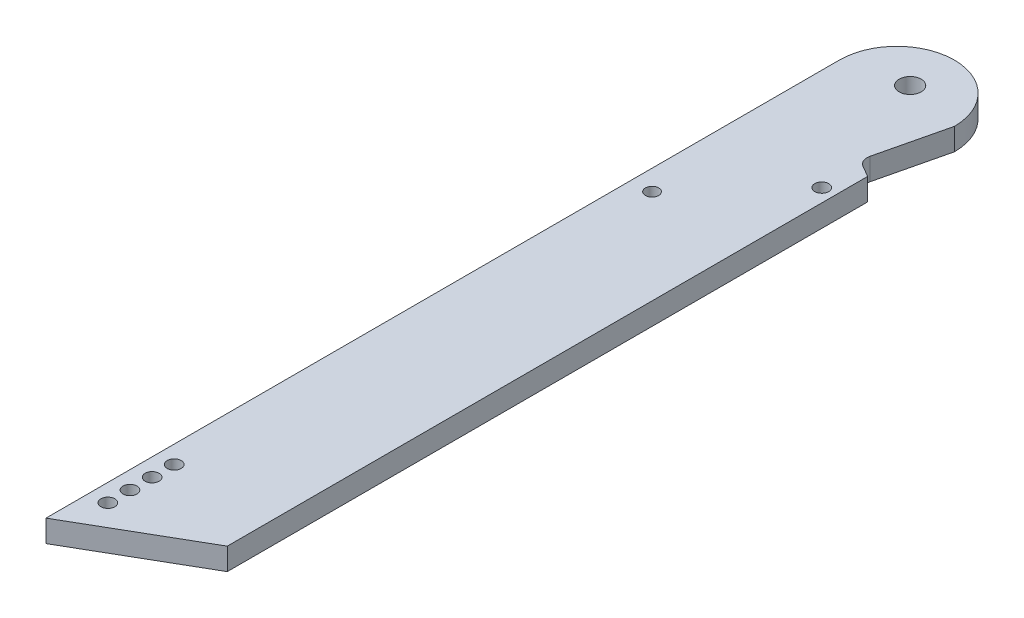
SolidWorks part; units mm, degrees
material "6061-T6 (SS)"
ref_plane "X-Y Datum" through (0, 0, 0) normal (0, 0, 1) x (1, 0, 0)
ref_plane "X-Z Datum" through (0, 0, 0) normal (0, 1, 0) x (1, 0, 0)
ref_plane "Y-Z Datum" through (0, 0, 0) normal (1, 0, 0) x (0, 0, -1)
other "Graphic1" [suppressed]
other "Graphic (Closed) -1" [suppressed]
sketch "Sketch2" plane through (0, 0, 0) normal (0, 1, 0) x (1, 0, 0)
  line L0 (-16.51, -3.81) -> (-16.51, -231.775)
  line L1 (-16.51, -231.775) -> (16.51, -212.7109)
  line L5 (-12.5603, 0) -> (-12.5603, -63.5) construction
  line L7 (11.8343, -23.3926) -> (16.51, -3.81)
  line L8 (0, 0) -> (0, -24.13) construction
  line L11 (0, -24.13) -> (18.0975, -24.13) construction
  line L13 (16.51, -212.7109) -> (16.51, -28.7127)
  line L14 (13.335, -26.8796) -> (16.51, -28.7127)
  circle A0 centre (0, 0) radius 3.175
  arc A1 (16.51, -3.81) -> (-16.51, -3.81) centre (0, -3.81) ccw
  circle A2 centre (-11.43, -219.075) radius 2
  circle A3 centre (-11.43, -212.725) radius 2
  circle A4 centre (-11.43, -206.375) radius 2
  circle A5 centre (-11.43, -200.025) radius 2
  circle A7 centre (0, 0) radius 12.5603 construction
  circle A8 centre (-10.6553, -63.5) radius 1.905
  circle A9 centre (14.9225, -24.13) radius 3.175 construction
  arc A11 (13.335, -26.8796) -> (11.8343, -23.3926) centre (14.9225, -24.13) cw
  circle A12 centre (12.7, -38.1) radius 2
  point P32 (18.0975, -24.13)
  dimension "D1" = 6.35
  dimension "D6" = 4
  dimension "D12" = 24.13
  dimension "D5" = 25.1206
  dimension "D14" = 3.81
  dimension "D19" = 4
  dimension "D20" = 6.35
  dimension "D2" = 227.965
  dimension "D3" = 3.81
  dimension "D4" = 33.02
  dimension "D7" = 6.35
  dimension "D8" = 6.35
  dimension "D9" = 6.35
  dimension "D10" = 5.08
  dimension "D11" = 12.7
  dimension "D13" = 18.0975
  dimension "D15" = 5.8547
  dimension "D16" = 63.5
  dimension "D17" = 33.02
  dimension "D18" = 120
  dimension "D21" = 3.81
  dimension "D22" = 38.1
  dimension "D23" = 120
extrude "Boss-Extrude1" add sketch "Sketch2" along normal blind 6.35
sketch "Sketch3" plane through (-16.51, 0, 0) normal (-1, 0, 0) x (0, 0, 1)
  line L0 (193.675, 6.35) -> (193.675, 0)
  line L1 (3.81, 6.35) -> (231.775, 6.35) construction
  line L2 (3.81, 0) -> (231.775, 0) construction
  line L4 (231.775, 6.35) -> (231.775, 0) construction
  dimension "1.5" = 38.1
split line "Split Line1"
